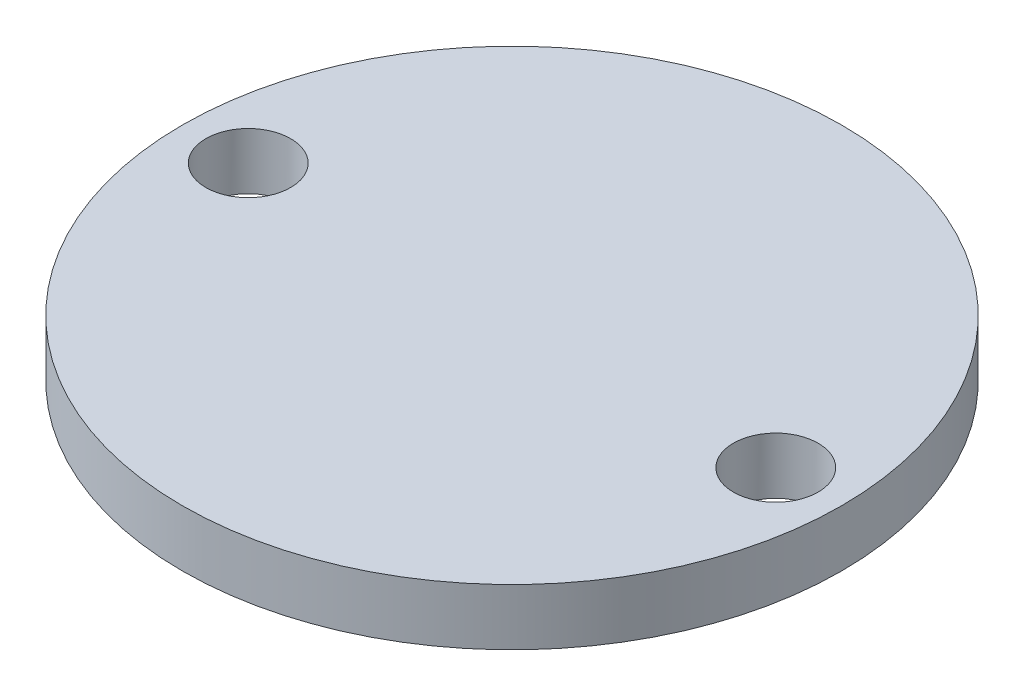
SolidWorks part; units mm, degrees
ref_plane "Alzado" through (0, 0, 0) normal (0, 0, 1) x (1, 0, 0)
ref_plane "Planta" through (0, 0, 0) normal (0, 1, 0) x (1, 0, 0)
ref_plane "Vista lateral" through (0, 0, 0) normal (1, 0, 0) x (0, 0, -1)
sketch "Croquis2" plane through (0, 0, 0) normal (0, 0, 1) x (1, 0, 0)
  line L0 (0, 0) -> (17.5, 0)
  line L1 (17.5, 0) -> (17.5, -3)
  line L2 (17.5, -3) -> (10, -3)
  line L3 (4.5, 0) -> (4.5, -11)
  line L4 (0, 0) -> (0, -13)
  arc A0 (4.5, -11) -> (10, -3) centre (-2.6877, -0.1678) ccw
  circle A1 centre (0, -6.9375) radius 6.0625
  point P12 (0, -13)
  dimension "D6" = 13
  dimension "D1" = 17.5
  dimension "D2" = 3
  dimension "D3" = 7.5
  dimension "D4" = 4.5
  dimension "D5" = 11
  dimension "D7" = 13
revolve "Revolución2" add sketch "Croquis2" angle 360 about L4
sketch "Croquis3" plane through (0, 0, 0) normal (0, 1, 0) x (1, 0, 0)
  circle A0 centre (14, 0) radius 2.25
  circle A1 centre (-14, 0) radius 2.25
  dimension "D1" = 4.5
  dimension "D2" = 4.5
  dimension "D3" = 14
  dimension "D4" = 14
extrude "Cortar-Extruir1" cut sketch "Croquis3" against normal through all
equation "\"D1@Croquis2\"=35/2"
equation "\"D2@Croquis3\"=\"D1@Croquis3\""
